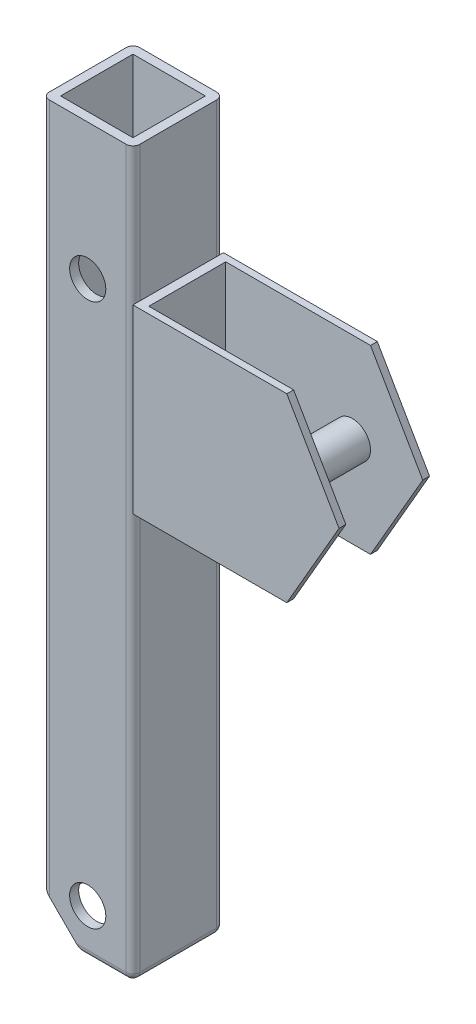
SolidWorks part; units mm, degrees
ref_plane "Front Plane" through (0, 0, 0) normal (0, 0, 1) x (1, 0, 0)
ref_plane "Top Plane" through (0, 0, 0) normal (0, 1, 0) x (1, 0, 0)
ref_plane "Right Plane" through (0, 0, 0) normal (1, 0, 0) x (0, 0, -1)
sketch "Sketch1" plane through (0, 0, 0) normal (0, 0, 1) x (1, 0, 0)
  line L1 (-5, 40) -> (5, 40)
  line L2 (-5, 40) -> (-5, -40)
  line L3 (-5, -40) -> (5, -40)
  line L4 (5, 40) -> (5, -40)
  line L5 (-5, 40) -> (5, -40) construction
  line L6 (-5, -40) -> (5, 40) construction
  point P0 (0, 0)
  dimension "D1" = 80
  dimension "D2" = 10
extrude "Boss-Extrude1" add sketch "Sketch1" along normal blind 10
shell "Shell1" thickness 1
fillet "Fillet1" radius 0.75 4 edges at (-5, 0, 0) (-5, 0, 10) (5, 0, 10) (5, 0, 0)
sketch "Sketch2" plane through (5, 0, 0) normal (1, 0, 0) x (0, 0, -1)
  line L0 (-9.25, 40) -> (-9.25, -40) construction
  line L1 (-9.25, 25) -> (-0.75, 25)
  line L2 (-9.25, 25) -> (-9.25, 5)
  line L3 (-9.25, 5) -> (-0.75, 5)
  line L4 (-0.75, 25) -> (-0.75, 5)
  line L5 (-0.75, -40) -> (-0.75, 40) construction
  line L6 (-9.25, 40) -> (-0.75, 40) construction
  dimension "D1" = 20
  dimension "D2" = 15
extrude "Boss-Extrude2" add sketch "Sketch2" along normal blind 1
sketch "Sketch3" plane through (5, 0, 0) normal (1, 0, 0) x (0, 0, -1)
  line L0 (-10, -40) -> (-10, 40) construction
  line L1 (-9.25, 25) -> (-10, 25)
  line L2 (-9.25, 25) -> (-9.25, 5)
  line L3 (-9.25, 5) -> (-10, 5)
  line L4 (-10, 25) -> (-10, 5)
  line L5 (0, 40) -> (0, -40) construction
  line L6 (-0.75, 5) -> (0, 5)
  line L7 (-0.75, 5) -> (-0.75, 25)
  line L8 (-0.75, 25) -> (0, 25)
  line L9 (0, 5) -> (0, 25)
  line L10 (-9.25, 40) -> (-0.75, 40) construction
  point P14 (-0.375, 25)
  dimension "D1" = 0.75
  dimension "D2" = 15
  dimension "D3" = 20
extrude "Boss-Extrude3" add sketch "Sketch3" along normal blind 30
sketch "Sketch4" plane through (0, 0, 10) normal (0, 0, 1) x (1, 0, 0)
  line L0 (22, 5) -> (35, 5)
  line L1 (35, 5) -> (5, 5) construction
  line L2 (35, 5) -> (35, 25)
  line L3 (35, 25) -> (22, 25)
  line L4 (35, 25) -> (5, 25) construction
  line L5 (22, 25) -> (27.7735, 15)
  line L6 (27.7735, 15) -> (22, 5)
  line L7 (5, 25) -> (5, 5) construction
  dimension "D1" = 60
  dimension "D2" = 17
  dimension "D3" = 17
  dimension "D4" = 60
extrude "Cut-Extrude1" cut sketch "Sketch4" against normal blind 35
sketch "Sketch5" plane through (0, 0, 10) normal (0, 0, 1) x (1, 0, 0)
  line L0 (4.25, 40) -> (-4.25, 40) construction
  line L1 (5, 25) -> (5, 5) construction
  line L2 (-4.25, -40) -> (4.25, -40) construction
  line L3 (4.25, -40) -> (4.25, 40) construction
  line L4 (-5, -35.5) -> (-0.5, -40)
  line L5 (-5, -40) -> (-5, 40) construction
  line L6 (-0.5, -40) -> (-5, -40)
  line L7 (-5, -40) -> (-5, -35.5)
  circle A0 centre (0, 25) radius 2
  circle A1 centre (0, -35) radius 2
  dimension "D1" = 4
  dimension "D3" = 5
  dimension "D4" = 4
  dimension "D2" = 15
  dimension "D5" = 5
  dimension "D6" = 4.25
  dimension "D7" = 45
  dimension "D8" = 4.5
extrude "Cut-Extrude2" cut sketch "Sketch5" against normal blind 35
fillet "Fillet2" radius 0.75 7 edges at (1.875, -40, 10) (4.7803, -40, 9.7803) (1.875, -40, 0) (4.7803, -40, 0.2197) (5, -40, 5) (-0.5, -40, 0.5) (-0.5, -40, 9.5)
sketch "Sketch6" plane through (0, 0, 10) normal (0, 0, 1) x (1, 0, 0)
  line L0 (22, 25) -> (5, 25) construction
  line L1 (5, 25) -> (5, 5) construction
  circle A0 centre (20, 15) radius 2
  dimension "D1" = 4
  dimension "D2" = 10
  dimension "D3" = 15
extrude "Boss-Extrude4" add sketch "Sketch6" against normal up to vertex (10 mm away) up to point (27.7735, 15, 0)
